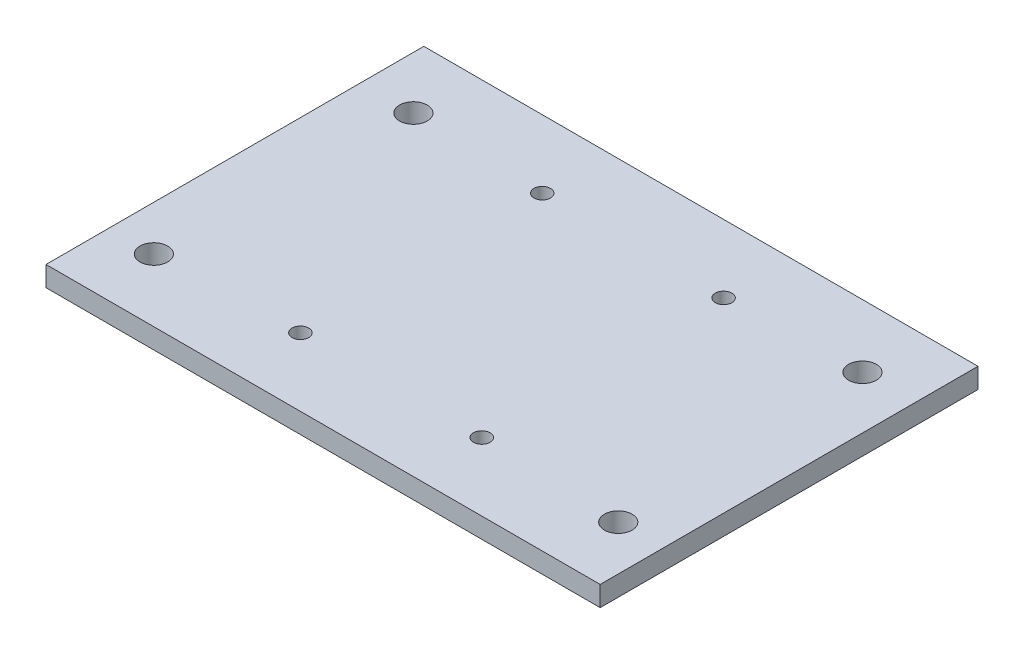
SolidWorks part; units mm, degrees
ref_plane "前基準面" through (0, 0, 0) normal (0, 0, 1) x (1, 0, 0)
ref_plane "上基準面" through (0, 0, 0) normal (0, 1, 0) x (1, 0, 0)
ref_plane "右基準面" through (0, 0, 0) normal (1, 0, 0) x (0, 0, -1)
sketch "草圖1" plane through (0, 0, 0) normal (0, 1, 0) x (1, 0, 0)
  line L0 (-55, 0) -> (55, 0) construction
  line L1 (-55, 37.5) -> (55, 37.5)
  line L2 (-55, 37.5) -> (-55, -37.5)
  line L3 (-55, -37.5) -> (55, -37.5)
  line L4 (55, 37.5) -> (55, -37.5)
  line L5 (0, -55) -> (0, 55) construction
  line L6 (-18, 24) -> (18, 24) construction
  line L7 (-18, 24) -> (-18, -24) construction
  line L8 (-18, -24) -> (18, -24) construction
  line L9 (18, 24) -> (18, -24) construction
  line L10 (-44.57, 25) -> (44.57, 25) construction
  line L11 (-46.095, -25) -> (46.095, -25) construction
  circle A0 centre (-18, 24) radius 1.65
  circle A1 centre (18, 24) radius 1.65
  circle A2 centre (-18, -24) radius 1.65
  circle A3 centre (18, -24) radius 1.65
  circle A4 centre (-44.57, 25) radius 2.75
  circle A5 centre (-46.095, -25) radius 2.75
  circle A6 centre (44.57, 25) radius 2.75
  circle A7 centre (46.095, -25) radius 2.75
  dimension "D7" = 3.3
  dimension "D8" = 3.3
  dimension "D9" = 3.3
  dimension "D10" = 3.3
  dimension "D17" = 5.5
  dimension "D18" = 5.5
  dimension "D19" = 5.5
  dimension "D20" = 5.5
  dimension "D1" = 75
  dimension "D2" = 37.5
  dimension "D3" = 48
  dimension "D4" = 24
  dimension "D5" = 36
  dimension "D6" = 18
  dimension "D11" = 89.14
  dimension "D12" = 44.57
  dimension "D13" = 25
  dimension "D14" = 25
  dimension "D15" = 92.19
  dimension "D16" = 46.095
  dimension "D21" = 110
  dimension "D22" = 55
extrude "填料-伸長1" add sketch "草圖1" along normal blind 4
